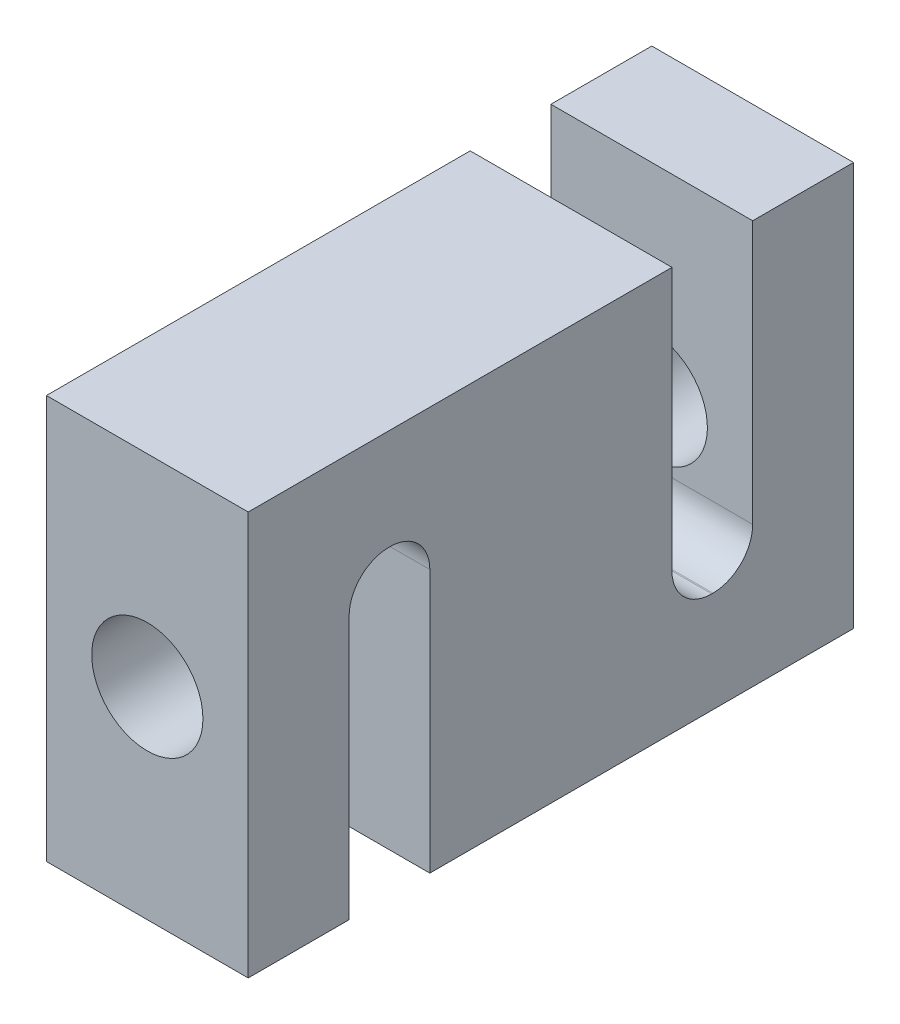
SolidWorks part; units mm, degrees
material "Plain Carbon Steel"
ref_plane "Front Plane" through (0, 0, 0) normal (0, 0, 1) x (1, 0, 0)
ref_plane "Top Plane" through (0, 0, 0) normal (0, 1, 0) x (1, 0, 0)
ref_plane "Right Plane" through (0, 0, 0) normal (1, 0, 0) x (0, 0, -1)
sketch "Sketch1" plane through (0, 0, 0) normal (0, 0, 1) x (1, 0, 0)
  line L1 (-15.0442, 30.1203) -> (10.3558, 30.1203)
  line L2 (-15.0442, 30.1203) -> (-15.0442, 80.9203)
  line L3 (-15.0442, 80.9203) -> (10.3558, 80.9203)
  line L4 (10.3558, 30.1203) -> (10.3558, 80.9203)
  dimension "D1" = 50.8
  dimension "D2" = 25.4
extrude "Boss-Extrude1" add sketch "Sketch1" along normal blind 76.2
sketch "Sketch2" plane through (-15.0442, 0, 0) normal (-1, 0, 0) x (0, 0, 1)
  line L0 (76.2, 80.9203) -> (0, 80.9203) construction
  line L1 (12.7, 80.9203) -> (22.86, 80.9203)
  line L2 (12.7, 80.9203) -> (12.7, 42.8203)
  line L3 (12.7, 42.8203) -> (22.86, 42.8203)
  line L4 (22.86, 80.9203) -> (22.86, 42.8203)
  line L5 (76.2, 30.1203) -> (0, 30.1203) construction
  line L6 (53.34, 30.1203) -> (63.5, 30.1203)
  line L7 (53.34, 30.1203) -> (53.34, 68.2203)
  line L8 (53.34, 68.2203) -> (63.5, 68.2203)
  line L9 (63.5, 30.1203) -> (63.5, 68.2203)
  line L10 (76.2, 80.9203) -> (76.2, 30.1203) construction
  line L11 (0, 80.9203) -> (0, 30.1203) construction
  point P16 (22.86, 42.8203)
  dimension "D1" = 12.7
  dimension "D2" = 12.7
  dimension "D3" = 10.16
  dimension "D4" = 10.16
  dimension "D5" = 38.1
  dimension "D6" = 38.1
extrude "Cut-Extrude1" cut sketch "Sketch2" against normal through all
sketch "Sketch5" plane through (0, 0, 0) normal (0, 0, -1) x (-1, 0, 0)
  line L0 (-10.3558, 30.1203) -> (15.0442, 80.9203) construction
  point P6 (2.3442, 55.5203)
hole_wizard "Tap Drill for M16x2.0 Tap2" positions "Sketch5" profile "Sketch4" hole size "M16x2.0" standard "ANSI Metric"
sketch "Sketch4" plane through (-2.3442, 55.5203, 0) normal (1, 0, 0) x (0, 1, 0)
  line L0 (0, 0) -> (0, 12.7)
  line L1 (0, 12.7) -> (7, 12.7)
  line L2 (7, 12.7) -> (7, 0)
  line L5 (7, 0) -> (0, 0)
  line L11 (0, -6.35) -> (0, 107.95) construction
  dimension "Thru Hole Dia." = 14
  dimension "Thru Hole Depth" = 12.7
sketch "Sketch8" plane through (0, 0, 76.2) normal (0, 0, 1) x (1, 0, 0)
  line L0 (-15.0442, 30.1203) -> (10.3558, 80.9203) construction
  point P7 (-2.3442, 55.5203)
hole_wizard "Tap Drill for M16x2.0 Tap1" positions "Sketch8" profile "Sketch7" hole size "M16x2.0" standard "ANSI Metric"
sketch "Sketch7" plane through (-2.3442, 55.5203, 76.2) normal (1, 0, 0) x (0, -1, 0)
  line L0 (0, 0) -> (0, 12.7)
  line L1 (0, 12.7) -> (7, 12.7)
  line L2 (7, 12.7) -> (7, 0)
  line L5 (7, 0) -> (0, 0)
  line L11 (0, -6.35) -> (0, 107.95) construction
  dimension "Thru Hole Dia." = 14
  dimension "Thru Hole Depth" = 12.7
fillet "Fillet1" radius 5 4 edges at (-2.3442, 42.8203, 12.7) (-2.3442, 42.8203, 22.86) (-2.3442, 68.2203, 63.5) (-2.3442, 68.2203, 53.34)
equation "\"D6@Sketch2\"=\"D5@Sketch2\""
equation "\"D3@Sketch2\"=\"D4@Sketch2\""
equation "\"D2@Sketch2\"=\"D1@Sketch2\""
